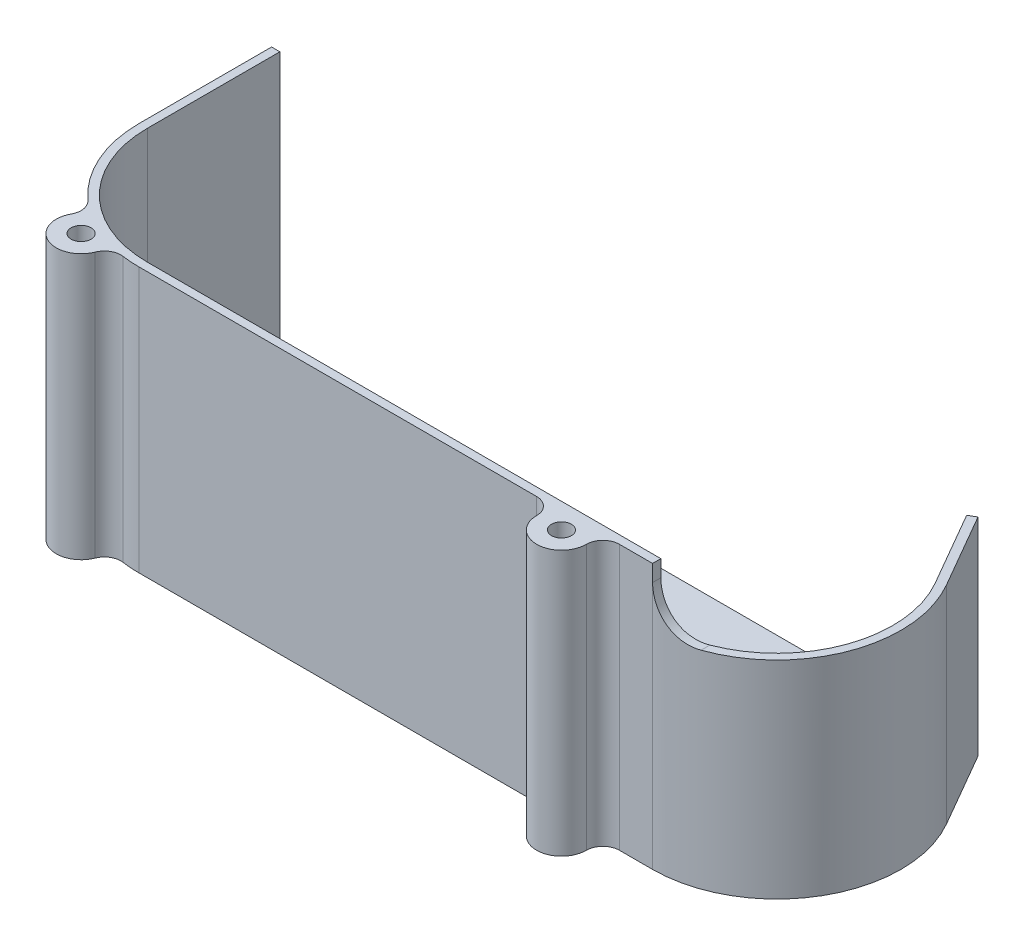
SolidWorks part; units mm, degrees
material "ABS"
ref_plane "Plan de face" through (0, 0, 0) normal (0, 0, 1) x (1, 0, 0)
ref_plane "Plan de dessus" through (0, 0, 0) normal (0, 1, 0) x (1, 0, 0)
ref_plane "Plan de droite" through (0, 0, 0) normal (1, 0, 0) x (0, 0, -1)
sketch "Esquisse1" plane through (0, 0, 0) normal (0, 1, 0) x (1, 0, 0)
  line L0 (-76, 30) -> (-76, 14)
  line L1 (-62, 0) -> (0, 0)
  line L2 (12.1244, 21) -> (6.9282, 30)
  arc A0 (-76, 14) -> (-62, 0) centre (-62, 14) ccw
  arc A1 (0, 0) -> (12.1244, 21) centre (0, 14) ccw
  dimension "D1" = 30
  dimension "D2" = 14
  dimension "D4" = 60
  dimension "D3" = 62
extrude "Extru.-Mince1" add sketch "Esquisse1" along normal blind 32 thin
sketch "Esquisse2" plane through (0, 0, 0) normal (0, 1, 0) x (1, 0, 0)
  line L0 (-76, 30) -> (6.9282, 30)
  line L1 (12.1244, 21) -> (6.9282, 30) construction
  line L2 (-62, 0) -> (0, 0) construction
  line L3 (-76, 30) -> (-76, 14) construction
  line L4 (12.1244, 21) -> (6.9282, 30)
  line L5 (-62, 0) -> (0, 0)
  line L6 (-76, 30) -> (-76, 14)
  arc A0 (0, 0) -> (12.1244, 21) centre (0, 14) ccw construction
  arc A1 (-76, 14) -> (-62, 0) centre (-62, 14) ccw construction
  arc A2 (0, 0) -> (12.1244, 21) centre (0, 14) ccw
  arc A3 (-76, 14) -> (-62, 0) centre (-62, 14) ccw
extrude "Boss.-Extru.1" add sketch "Esquisse2" along normal blind 1
sketch "Esquisse3" plane through (0, 0, 0) normal (0, 1, 0) x (1, 0, 0)
  line L0 (-62, -1) -> (0, -1) construction
  line L1 (-11.2361, -1) -> (-6.7639, -1)
  line L6 (-62, 0) -> (0, 0) construction
  circle A0 centre (-69, -1) radius 1.2
  circle A1 centre (-9, -3) radius 1.2
  arc A2 (-70.4659, 1.6174) -> (-66.0523, -0.4423) centre (-69, -1) ccw
  arc A3 (-11.2361, -1) -> (-6.7639, -1) centre (-9, -3) ccw
  arc A4 (-77, 14) -> (-62, -1) centre (-62, 14) ccw construction
  arc A6 (-70.4659, 1.6174) -> (-66.0523, -0.4423) centre (-62, 14) ccw
  dimension "D1" = 1
  dimension "D2" = 7
  dimension "D3" = 2
  dimension "D4" = 2.4
  dimension "D5" = 6
  dimension "D6" = 60
extrude "Boss.-Extru.2" add sketch "Esquisse3" along normal up to surface (32 mm away) up to face at (-31.9676, 32, -14.6453)
fillet "Congé1" radius 2 4 edges at (-70.4659, 16, -1.6174) (-66.0523, 16, 0.4423) (-11.2361, 16, 1) (-6.7639, 16, 1)
sketch "Esquisse4" plane through (-7.9393, 0, 1) normal (0, 0, -1) x (-1, 0, 0)
  line L1 (-22.9393, 32) -> (-7.9393, 32)
  line L2 (-22.9393, 32) -> (-22.9393, 25)
  line L3 (-22.9393, 25) -> (-12.9393, 25)
  line L4 (-7.9393, 32) -> (-7.9393, 30)
  line L5 (54.0607, 32) -> (-7.9393, 32) construction
  line L6 (-22.9393, 32) -> (-22.9393, 0) construction
  arc A0 (-12.9393, 25) -> (-7.9393, 30) centre (-12.9393, 30) ccw
  dimension "D1" = 5
  dimension "D2" = 15
  dimension "D3" = 7
extrude "Enlèv. mat.-Extru.1" cut sketch "Esquisse4" along normal through all
